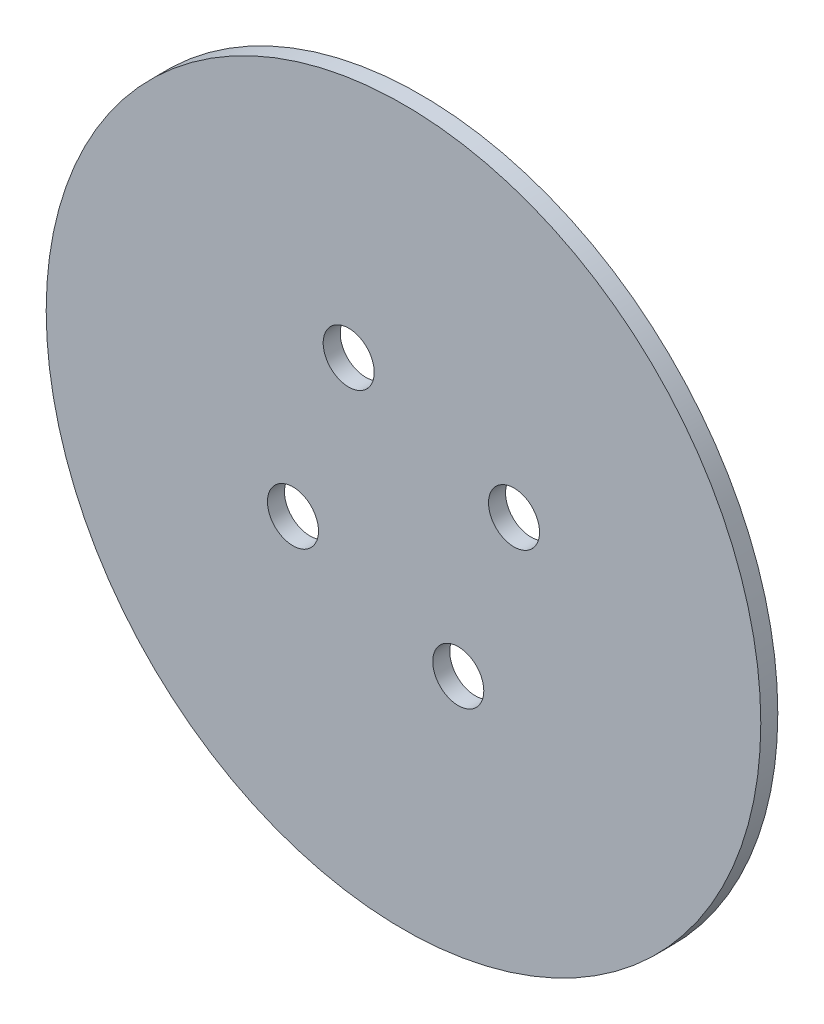
SolidWorks part; units mm, degrees
ref_plane "Front Plane" through (0, 0, 0) normal (0, 0, 1) x (1, 0, 0)
ref_plane "Top Plane" through (0, 0, 0) normal (0, 1, 0) x (1, 0, 0)
ref_plane "Right Plane" through (0, 0, 0) normal (1, 0, 0) x (0, 0, -1)
sketch "Sketch1" plane through (0, 0, 0) normal (0, 0, 1) x (1, 0, 0)
  circle A0 centre (0, 0) radius 21
extrude "Boss-Extrude1" add sketch "Sketch1" along normal blind 1
sketch "Sketch2" plane through (0, 0, 1) normal (0, 0, 1) x (1, 0, 0)
  circle A0 centre (-3.2196, 6.4959) radius 1.5
  circle A1 centre (6.4959, 3.2196) radius 1.5
  circle A2 centre (-6.4959, -3.2196) radius 1.5
  circle A3 centre (3.2196, -6.4959) radius 1.5
extrude "Cut-Extrude1" cut sketch "Sketch2" against normal through all
